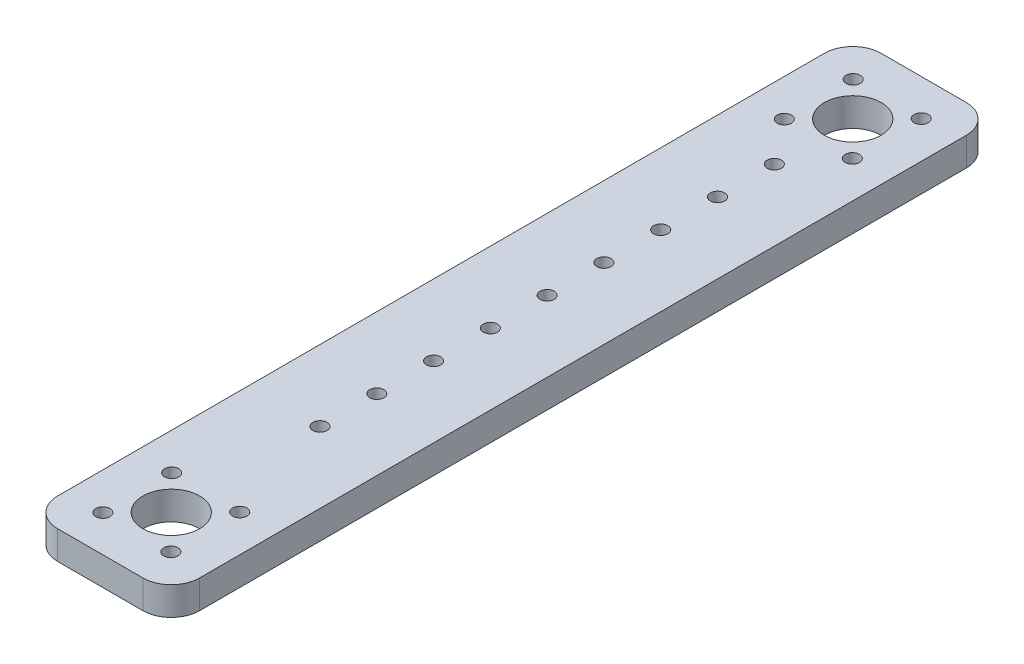
SolidWorks part; units mm, degrees
ref_plane "Front Plane" through (0, 0, 0) normal (0, 0, 1) x (1, 0, 0)
ref_plane "Top Plane" through (0, 0, 0) normal (0, 1, 0) x (1, 0, 0)
ref_plane "Right Plane" through (0, 0, 0) normal (1, 0, 0) x (0, 0, -1)
sketch "Sketch2" plane through (0, 0, 0) normal (0, 1, 0) x (1, 0, 0)
  line L1 (0, 0) -> (-127, 0)
  line L2 (0, 0) -> (0, 736.6)
  line L3 (0, 736.6) -> (-127, 736.6)
  line L4 (-127, 0) -> (-127, 736.6)
  dimension "D1" = 127
  dimension "D2" = 736.6
extrude "Boss-Extrude1" add sketch "Sketch2" along normal blind 25.4 contours L3 L4 L1 L2
hole_wizard "1/2 (0.5) Diameter Hole1" positions "Sketch3" profile "Sketch4" hole size "1/2" standard "ANSI Inch" end condition through all
sketch "Sketch3" plane through (0, 25.4, 0) normal (0, 1, 0) x (1, 0, 0)
  line L0 (0, 736.6) -> (-127, 736.6) construction
  line L1 (0, 0) -> (0, 736.6) construction
  line L2 (0, 368.3) -> (-127, 368.3)
  line L3 (-127, 0) -> (-127, 736.6) construction
  point P0 (-63.5, 673.1)
  point P14 (-63.5, 63.5)
  dimension "D1" = 63.5
  dimension "D2" = 63.5
sketch "Sketch4" plane through (-63.5, 25.4, -673.1) normal (1, 0, 0) x (0, 0, 1)
  line L0 (0, 0) -> (0, 25.4)
  line L1 (0, 25.4) -> (25.4, 25.4)
  line L2 (25.4, 25.4) -> (25.4, 0)
  line L5 (25.4, 0) -> (0, 0)
  line L11 (0, -6.35) -> (0, 107.95) construction
  dimension "Thru Hole Dia." = 50.8
  dimension "Thru Hole Depth" = 25.4
hole_wizard "1/2 (0.5) Diameter Hole2" positions "Sketch7" profile "Sketch6" hole size "1/2" standard "ANSI Inch" end condition through all
sketch "Sketch7" plane through (0, 25.4, 0) normal (0, 1, 0) x (1, 0, 0)
  line L0 (-63.5, 736.6) -> (-63.5, 647.7) construction
  line L1 (0, 736.6) -> (-127, 736.6) construction
  line L3 (-38.1, 673.1) -> (0, 673.1) construction
  line L4 (0, 0) -> (0, 736.6) construction
  line L5 (0, 368.3) -> (-127, 368.3)
  line L6 (-127, 0) -> (-127, 736.6) construction
  circle A0 centre (-63.5, 673.1) radius 25.4 construction
  point P0 (-93.9235, 703.916)
  point P17 (-33.0765, 703.916)
  point P18 (-33.0765, 642.284)
  point P19 (-93.9235, 642.284)
  point P20 (-63.5, 602.9372)
  point P28 (-63.5, 552.1372)
  point P29 (-63.5, 501.3372)
  point P30 (-63.5, 450.5372)
  point P31 (-63.5, 399.7372)
  point P32 (-63.5, 348.9372)
  point P33 (-63.5, 298.1372)
  point P34 (-63.5, 247.3372)
  point P35 (-63.5, 196.5372)
  point P43 (-93.9235, 32.684)
  point P44 (-93.9235, 94.316)
  point P45 (-33.0765, 94.316)
  point P46 (-33.0765, 32.684)
  dimension "D1" = 9
sketch "Sketch6" plane through (-93.9235, 25.4, -703.916) normal (1, 0, 0) x (0, 0, 1)
  line L0 (0, 0) -> (0, 25.4)
  line L1 (0, 25.4) -> (6.35, 25.4)
  line L2 (6.35, 25.4) -> (6.35, 0)
  line L5 (6.35, 0) -> (0, 0)
  line L11 (0, -6.35) -> (0, 107.95) construction
  dimension "Thru Hole Dia." = 12.7
  dimension "Thru Hole Depth" = 25.4
fillet "Fillet1" radius 25.4 4 edges at (-127, 12.7, 0) (0, 12.7, 0) (-127, 12.7, -736.6) (0, 12.7, -736.6)
